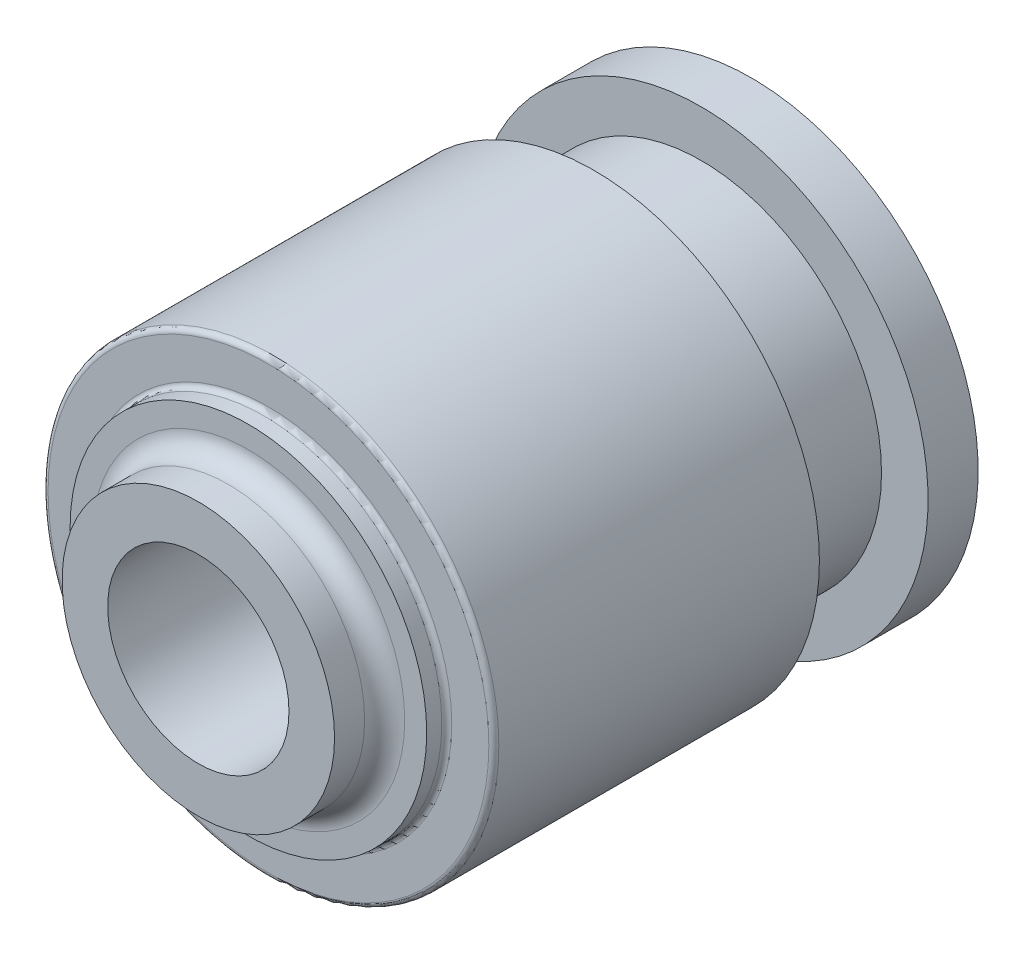
SolidWorks part; units mm, degrees
ref_plane "Ön Düzlem" through (0, 0, 0) normal (0, 0, 1) x (1, 0, 0)
ref_plane "Üst Düzlem" through (0, 0, 0) normal (0, 1, 0) x (1, 0, 0)
ref_plane "Sağ Düzlem" through (0, 0, 0) normal (1, 0, 0) x (0, 0, -1)
sketch "Çizim1" plane through (0, 0, 0) normal (0, 0, 1) x (1, 0, 0)
  circle A0 centre (0, 0) radius 22.5
  dimension "D1" = 45
extrude "Yükseklik-Ekstrüzyon1" add sketch "Çizim1" along normal blind 32.5
sketch "Çizim2" plane through (0, 0, 32.5) normal (0, 0, 1) x (1, 0, 0)
  circle A0 centre (0, 0) radius 17.8
  dimension "D1" = 35.6
extrude "Yükseklik-Ekstrüzyon2" add sketch "Çizim2" along normal blind 2
fillet "Radyus1" radius 0.5 1 edges at (17.8, 0, 32.5)
sketch "Çizim3" plane through (0, 0, 34.5) normal (0, 0, 1) x (1, 0, 0)
  circle A0 centre (0, 0) radius 13.6
  dimension "D1" = 27.2
extrude "Yükseklik-Ekstrüzyon3" add sketch "Çizim3" along normal blind 5
fillet "Radyus2" radius 2 1 edges at (13.6, 0, 34.5)
sketch "Çizim4" plane through (0, 0, 39.5) normal (0, 0, 1) x (1, 0, 0)
  circle A0 centre (0, 0) radius 9.05
  dimension "D1" = 18.1
extrude "Kes-Ekstrüzyon1" cut sketch "Çizim4" against normal blind 20
fillet "Radyus3" radius 0.5 1 edges at (22.5, 0, 32.5)
sketch "Çizim5" plane through (0, 0, 0) normal (0, 0, -1) x (-1, 0, 0)
  circle A0 centre (0, 0) radius 18
  dimension "D1" = 36
extrude "Yükseklik-Ekstrüzyon4" add sketch "Çizim5" along normal blind 10.7
sketch "Çizim6" plane through (0, 0, -10.7) normal (0, 0, -1) x (-1, 0, 0)
  circle A0 centre (0, 0) radius 22.65
  dimension "D1" = 45.3
extrude "Yükseklik-Ekstrüzyon5" add sketch "Çizim6" along normal blind 5
sketch "Çizim7" plane through (0, 0, -15.7) normal (0, 0, -1) x (-1, 0, 0)
  line L0 (-6.5, -6.5) -> (-6.5, 6.5)
  line L1 (-8, -8) -> (8, -8)
  line L2 (-8, -8) -> (-8, 8)
  line L3 (-8, 8) -> (8, 8)
  line L4 (8, -8) -> (8, 8)
  line L5 (-8, -8) -> (8, 8) construction
  line L6 (-8, 8) -> (8, -8) construction
  line L7 (-6.5, 6.5) -> (6.5, 6.5)
  line L8 (6.5, -6.5) -> (6.5, 6.5)
  line L9 (-6.5, -6.5) -> (6.5, -6.5)
  point P0 (0, 0)
  dimension "D1" = 16
  dimension "D2" = 1.5
extrude "Yükseklik-Ekstrüzyon6" add sketch "Çizim7" along normal blind 4
